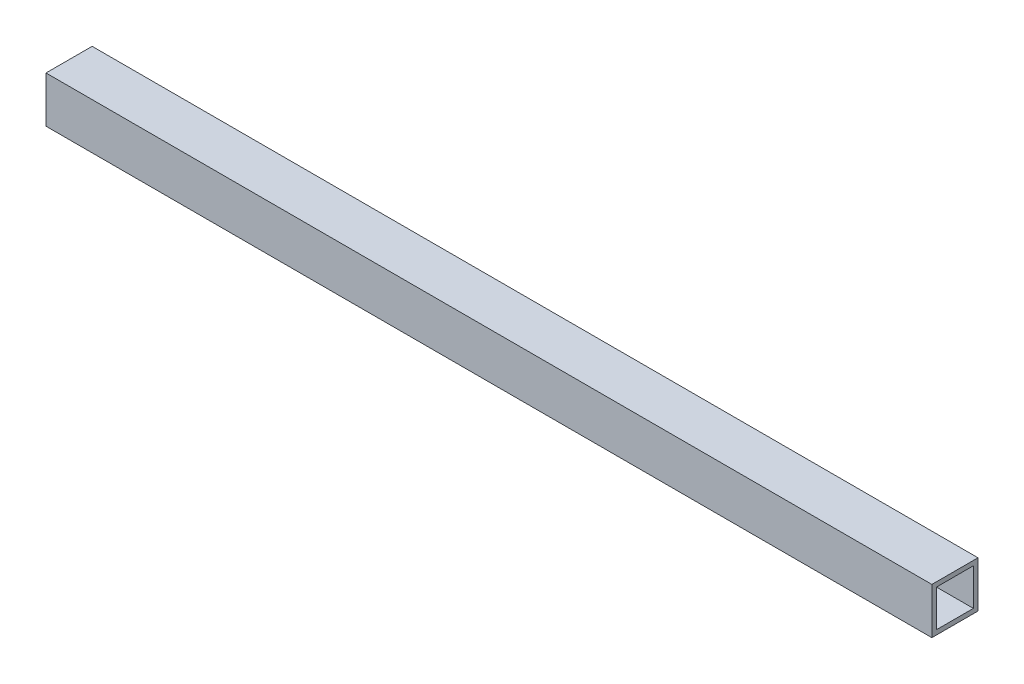
SolidWorks part; units mm, degrees
ref_plane "Front Plane" through (0, 0, 0) normal (0, 0, 1) x (1, 0, 0)
ref_plane "Top Plane" through (0, 0, 0) normal (0, 1, 0) x (1, 0, 0)
ref_plane "Right Plane" through (0, 0, 0) normal (1, 0, 0) x (0, 0, -1)
sketch "Sketch1" plane through (0, 0, 0) normal (1, 0, 0) x (0, 0, -1)
  line L0 (0, 0) -> (31.75, 0)
  line L1 (31.75, 0) -> (31.75, 31.75)
  line L2 (31.75, 31.75) -> (0, 31.75)
  line L3 (0, 31.75) -> (0, 0)
  line L4 (3.175, 28.575) -> (3.175, 3.175)
  line L5 (3.175, 3.175) -> (28.575, 3.175)
  line L6 (28.575, 3.175) -> (28.575, 28.575)
  line L7 (28.575, 28.575) -> (3.175, 28.575)
  dimension "D1" = 31.75
  dimension "D2" = 31.75
  dimension "D3" = 3.175
  dimension "D4" = 3.175
  dimension "D5" = 3.175
  dimension "D6" = 3.175
extrude "Boss-Extrude1" add sketch "Sketch1" along normal blind 609.6
